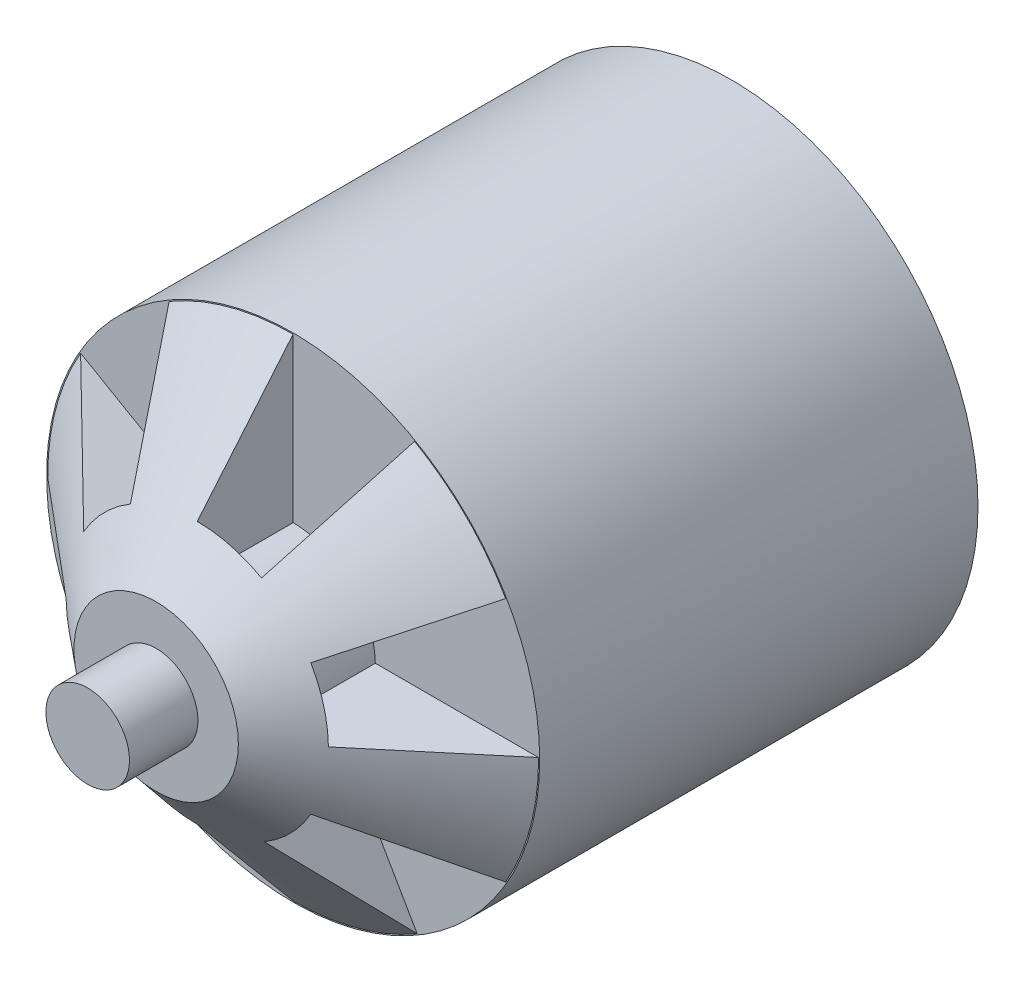
SolidWorks part; units mm, degrees
ref_plane "前视基准面" through (0, 0, 0) normal (0, 0, 1) x (1, 0, 0)
ref_plane "上视基准面" through (0, 0, 0) normal (0, 1, 0) x (1, 0, 0)
ref_plane "右视基准面" through (0, 0, 0) normal (1, 0, 0) x (0, 0, -1)
other "Configuration Table"
sketch "草图1" plane through (0, 0, 0) normal (0, 0, 1) x (1, 0, 0)
  circle A0 centre (0, 0) radius 18
  dimension "D1" = 36
extrude "凸台-拉伸1" add sketch "草图1" along normal blind 32
sketch "草图2" plane through (0, 0, 0) normal (0, 0, -1) x (-1, 0, 0)
  line L0 (0, 0) -> (-10.2071, 0) construction
  line L1 (0, 0) -> (0, 8.2721) construction
  circle A0 centre (-8.5, 0) radius 1.5
  circle A1 centre (8.5, 0) radius 1.5
  circle A2 centre (0, 12.5) radius 1.5
  circle A3 centre (0, -12.5) radius 1.5
  dimension "D1" = 3
  dimension "D3" = 3
  dimension "D2" = 8.5
  dimension "D4" = 12.5
extrude "切除-拉伸1" cut sketch "草图2" against normal blind 3
ref_plane "基准面1" through (0, 0, 42) normal (0, 0, 1) x (1, 0, 0)
sketch "草图5" plane through (0, 0, 42) normal (0, 0, 1) x (1, 0, 0)
  circle A0 centre (0, 0) radius 6
  dimension "D1" = 12
extrude "凸台-拉伸5" add sketch "草图5" against normal blind 10 draft 50 separate body draft outward yes
sketch "草图7" plane through (0, 0, 32) normal (0, 0, -1) x (-1, 0, 0)
  line L0 (0, -6) -> (0, -17.9175)
  line L1 (2.9047, -5.25) -> (8.8638, -15.5715)
  line L2 (-3.0943, -5.1406) -> (-9.0534, -15.462)
  line L3 (-5.1962, -3) -> (-15.517, -8.9588)
  line L4 (-5.999, 0.1094) -> (-17.9172, 0.1094)
  line L5 (-5.1962, 3) -> (-15.517, 8.9588)
  line L6 (-2.9047, 5.25) -> (-8.8638, 15.5715)
  line L7 (0, 6) -> (0, 17.9175)
  line L8 (3.0943, 5.1406) -> (9.0534, 15.462)
  line L9 (5.1962, 3) -> (15.517, 8.9588)
  line L10 (5.999, -0.1094) -> (17.9172, -0.1094)
  line L11 (5.1962, -3) -> (15.517, -8.9588)
  circle A0 centre (0, 0) radius 6 construction
  circle A1 centre (0, 0) radius 17.9175 construction
  arc A2 (0, -17.9175) -> (8.8638, -15.5715) centre (0, 0) ccw
  arc A3 (0, -6) -> (2.9047, -5.25) centre (0, 0) ccw
  arc A4 (-5.1962, -3) -> (-3.0943, -5.1406) centre (0, 0) ccw
  arc A5 (-15.517, -8.9588) -> (-9.0534, -15.462) centre (0, 0) ccw
  arc A6 (-5.1962, 3) -> (-5.999, 0.1094) centre (0, 0) ccw
  arc A7 (-15.517, 8.9588) -> (-17.9172, 0.1094) centre (0, 0) ccw
  arc A8 (0, 6) -> (-2.9047, 5.25) centre (0, 0) ccw
  arc A9 (0, 17.9175) -> (-8.8638, 15.5715) centre (0, 0) ccw
  arc A10 (5.1962, 3) -> (3.0943, 5.1406) centre (0, 0) ccw
  arc A11 (15.517, 8.9588) -> (9.0534, 15.462) centre (0, 0) ccw
  arc A12 (5.1962, -3) -> (5.999, -0.1094) centre (0, 0) ccw
  arc A13 (15.517, -8.9588) -> (17.9172, -0.1094) centre (0, 0) ccw
  point P31 (0, 0)
  dimension "D1" = 30
  dimension "D2" = 3
  dimension "D3" = 6
extrude "切除-拉伸2" cut sketch "草图7" against normal blind 7
sketch "草图8" plane through (0, 0, 42) normal (0, 0, 1) x (1, 0, 0)
  circle A0 centre (0, 0) radius 3.05
  dimension "D1" = 6.1
extrude "凸台-拉伸6" add sketch "草图8" along normal blind 5
